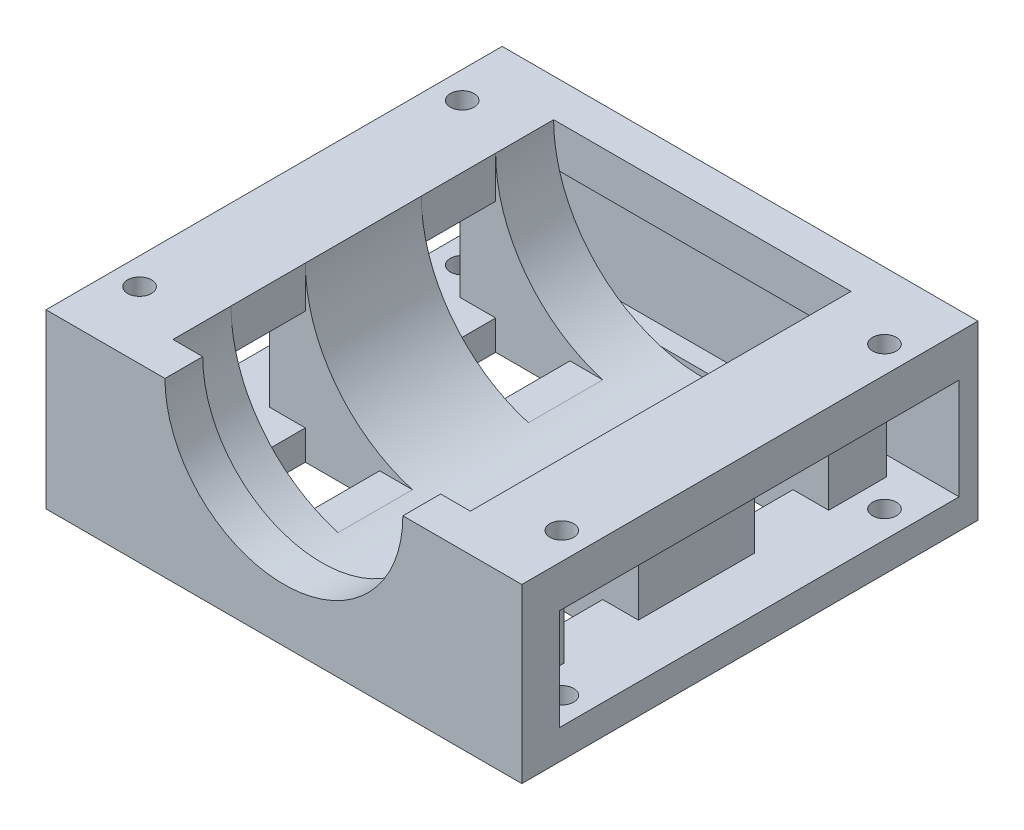
SolidWorks part; units mm, degrees
material "6061 Alloy"
ref_plane "Front Plane" through (0, 0, 0) normal (0, 0, 1) x (1, 0, 0)
ref_plane "Top Plane" through (0, 0, 0) normal (0, 1, 0) x (1, 0, 0)
ref_plane "Right Plane" through (0, 0, 0) normal (1, 0, 0) x (0, 0, -1)
sketch "Sketch1" plane through (0, 0, 0) normal (0, 0, 1) x (1, 0, 0)
  line L0 (0, 0) -> (80, 0)
  line L1 (80, 0) -> (80, 5)
  line L2 (80, 5) -> (71, 5)
  line L3 (71, 5) -> (71, 22)
  line L4 (80, 29) -> (65, 29)
  line L7 (15, 29) -> (0, 29)
  line L8 (9, 22) -> (9, 5)
  line L9 (9, 5) -> (0, 5)
  line L10 (0, 5) -> (0, 0)
  line L12 (0, 29) -> (0, 22)
  line L13 (0, 22) -> (9, 22)
  line L14 (80, 29) -> (80, 22)
  line L15 (80, 22) -> (71, 22)
  arc A0 (15, 29) -> (65, 29) centre (40, 29) ccw
  dimension "D1" = 50
  dimension "D2" = 9
  dimension "D3" = 5
  dimension "D4" = 7
  dimension "D5" = 15
  dimension "D6" = 17
extrude "Boss-Extrude1" add sketch "Sketch1" along normal blind 64
ref_plane "Plane1" through (0, 0, 64) normal (0, 0, 1) x (1, 0, 0)
sketch "Sketch2" plane through (0, 0, 64) normal (0, 0, 1) x (1, 0, 0)
  line L0 (60, 29) -> (80, 29)
  line L1 (0, 0) -> (80, 0)
  line L2 (0, 0) -> (0, 29)
  line L3 (0, 29) -> (20, 29)
  line L4 (80, 0) -> (80, 29)
  line L5 (40, 0) -> (40, 29) construction
  arc A0 (20, 29) -> (60, 29) centre (40, 29) ccw
  dimension "D1" = 40
extrude "Boss-Extrude2" add sketch "Sketch2" along normal blind 6.35
ref_plane "Plane2" through (0, 29, 0) normal (0, 1, 0) x (1, 0, 0)
sketch "Sketch3" plane through (0, 29, 0) normal (0, 1, 0) x (1, 0, 0)
  line L0 (15, -64) -> (15, 0) construction
  line L1 (15, -9.75) -> (27.5, -9.75)
  line L2 (15, -9.75) -> (15, -22.25)
  line L3 (15, -22.25) -> (27.5, -22.25)
  line L4 (27.5, -9.75) -> (27.5, -22.25)
  line L5 (40, 0) -> (40, -64) construction
  line L6 (65, 0) -> (15, 0) construction
  line L7 (-15.95, -64) -> (15.95, -64) construction
  line L8 (40, -32) -> (15, -32) construction
  line L9 (15, 0) -> (65, -64) construction
  line L10 (65, 0) -> (15, -64) construction
  line L11 (15, -32) -> (40, 0) construction
  line L12 (27.5, -16) -> (15, -16) construction
  line L13 (65, -64) -> (65, 0) construction
  line L14 (65, -64) -> (60, -64) construction
  line L15 (65, -22.25) -> (52.5, -22.25)
  line L16 (52.5, -9.75) -> (52.5, -22.25)
  line L17 (65, -9.75) -> (52.5, -9.75)
  line L18 (65, -9.75) -> (65, -22.25)
  line L19 (15, -41.75) -> (27.5, -41.75)
  line L20 (27.5, -54.25) -> (27.5, -41.75)
  line L21 (15, -54.25) -> (27.5, -54.25)
  line L22 (15, -54.25) -> (15, -41.75)
  line L23 (65, -54.25) -> (65, -41.75)
  line L24 (65, -54.25) -> (52.5, -54.25)
  line L25 (52.5, -54.25) -> (52.5, -41.75)
  line L26 (65, -41.75) -> (52.5, -41.75)
  point P23 (15, -16)
extrude "Cut-Extrude1" cut sketch "Sketch3" against normal up to surface (29 mm away) up to face at (40, 0, 35.175)
ref_plane "Plane3" through (15, 0, 0) normal (1, 0, 0) x (0, 0, -1)
sketch "Sketch5" plane through (15, 0, 0) normal (1, 0, 0) x (0, 0, -1)
  line L0 (-54.25, 0) -> (-54.25, 29) construction
  line L1 (-54.25, 22) -> (-41.75, 22)
  line L2 (-54.25, 22) -> (-54.25, 5)
  line L3 (-54.25, 5) -> (-41.75, 5)
  line L4 (-41.75, 22) -> (-41.75, 5)
  line L5 (-41.75, 0) -> (-41.75, 29) construction
  line L8 (-54.25, 22) -> (-54.25, 29) construction
  line L9 (-54.25, 0) -> (-54.25, 5) construction
  line L16 (-22.25, 22) -> (-9.75, 22)
  line L17 (-22.25, 22) -> (-22.25, 5)
  line L18 (-22.25, 5) -> (-9.75, 5)
  line L19 (-9.75, 22) -> (-9.75, 5)
  line L20 (-22.25, 0) -> (-22.25, 7.3494) construction
  line L21 (-9.75, 0) -> (-9.75, 29) construction
  dimension "D1" = 7
  dimension "D2" = 5
extrude "Cut-Extrude2" cut sketch "Sketch5" against normal up to surface and the other way up to surface up to face at (9, 13.5, 32) other way up to face at (71, 13.5, 32)
ref_plane "Plane4" through (0, 0, 0) normal (0, -1, 0) x (-1, 0, 0)
sketch "Sketch6" plane through (0, 0, 0) normal (0, -1, 0) x (-1, 0, 0)
  line L0 (-4.8728, -32) -> (0, -32) construction
  line L1 (-15, 0) -> (-15, -70.35) construction
  line L2 (-15, 15.95) -> (-15, -15.95) construction
  line L3 (0, -70.35) -> (-80, -70.35) construction
  line L4 (-15, -54.25) -> (0, -64) construction
  line L5 (-27.5, -54.25) -> (-15, -54.25) construction
  line L7 (0, -70.35) -> (0, 0) construction
  line L9 (0, 0) -> (-80, 0) construction
  line L10 (-40, -70.35) -> (-40, 0) construction
  line L11 (0, -64) -> (-15, -64) construction
  line L12 (-15.95, -64) -> (15.95, -64) construction
  line L13 (0, -64) -> (-15, 0) construction
  line L14 (0, -64) -> (-8.9998, -64) construction
  line L15 (-8.9998, -64) -> (-8.9998, -54.25) construction
  line L16 (-8.9998, -54.25) -> (0, -54.25) construction
  line L17 (0, -54.25) -> (-8.9998, -64) construction
  line L18 (0, -64) -> (-8.9998, -54.25) construction
  circle A0 centre (-4.4999, -59.125) radius 2
  circle A1 centre (-4.4999, -4.875) radius 2
  circle A2 centre (-75.5001, -4.875) radius 2
  circle A3 centre (-75.5001, -59.125) radius 2
  point P13 (-4.4999, -59.125)
  dimension "D1" = 4
extrude "Cut-Extrude3" cut sketch "Sketch6" against normal up to surface (29 mm away) up to face at (67, 29, 39.67)
ref_plane "Plane5" through (0, 0, 0) normal (0, 0, -1) x (-1, 0, 0)
sketch "Sketch7" plane through (0, 0, 0) normal (0, 0, -1) x (-1, 0, 0)
  line L1 (-80, 0) -> (0, 0)
  line L2 (-80, 0) -> (-80, 29)
  line L3 (-80, 29) -> (0, 29)
  line L4 (0, 0) -> (0, 29)
extrude "Boss-Extrude3" add sketch "Sketch7" along normal blind 6.35
ref_plane "Plane6" through (80, 0, 0) normal (1, 0, 0) x (0, 0, -1)
sketch "Sketch8" plane through (80, 0, 0) normal (1, 0, 0) x (0, 0, -1)
  line L0 (0, 5) -> (6.35, 5) construction
  line L1 (0, 22) -> (3.175, 22)
  line L2 (0, 22) -> (0, 5)
  line L3 (0, 5) -> (3.175, 5)
  line L4 (3.175, 22) -> (3.175, 5)
  line L5 (6.35, 29) -> (6.35, 0) construction
  line L6 (0, 22) -> (6.35, 5) construction
  line L8 (0, 5) -> (6.35, 22) construction
  point P2 (3.175, 13.5)
  point P12 (3.175, 13.5)
extrude "Cut-Extrude4" cut sketch "Sketch8" against normal up to surface (80 mm away) up to face at (0, 14.5, 32)
